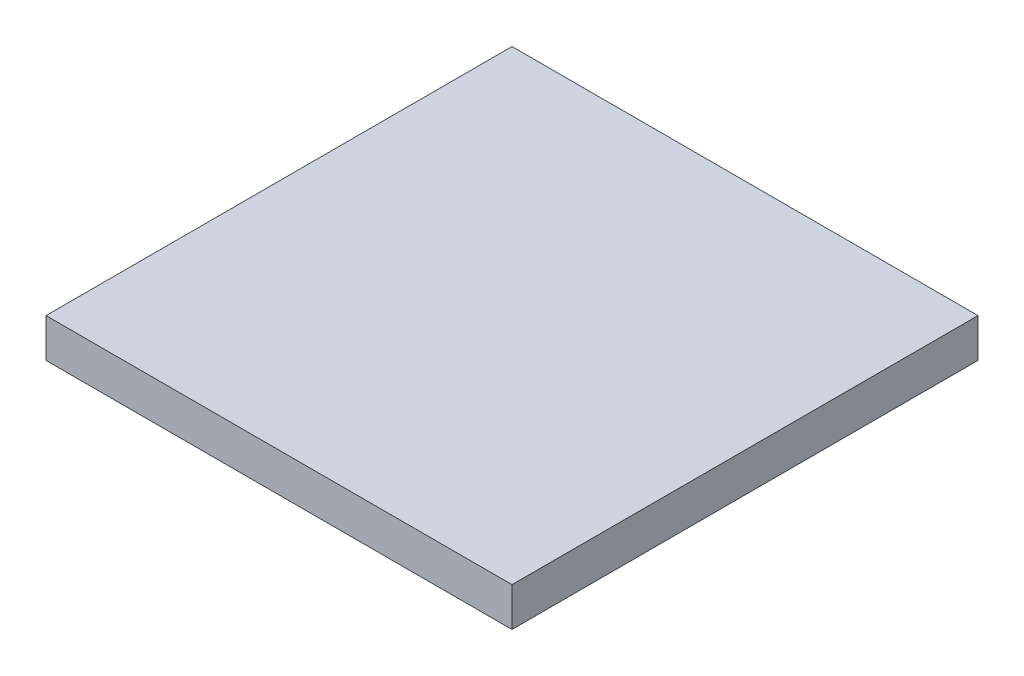
SolidWorks part; units mm, degrees
ref_plane "Front Plane" through (0, 0, 0) normal (0, 0, 1) x (1, 0, 0)
ref_plane "Top Plane" through (0, 0, 0) normal (0, 1, 0) x (1, 0, 0)
ref_plane "Right Plane" through (0, 0, 0) normal (1, 0, 0) x (0, 0, -1)
sketch "Sketch1" plane through (0, 0, 0) normal (0, 1, 0) x (1, 0, 0)
  line L1 (0, 0) -> (60, 0)
  line L2 (0, 0) -> (0, 60)
  line L3 (0, 60) -> (60, 60)
  line L4 (60, 0) -> (60, 60)
  dimension "D1" = 60
  dimension "D2" = 60
extrude "Boss-Extrude1" add sketch "Sketch1" along normal blind 5
